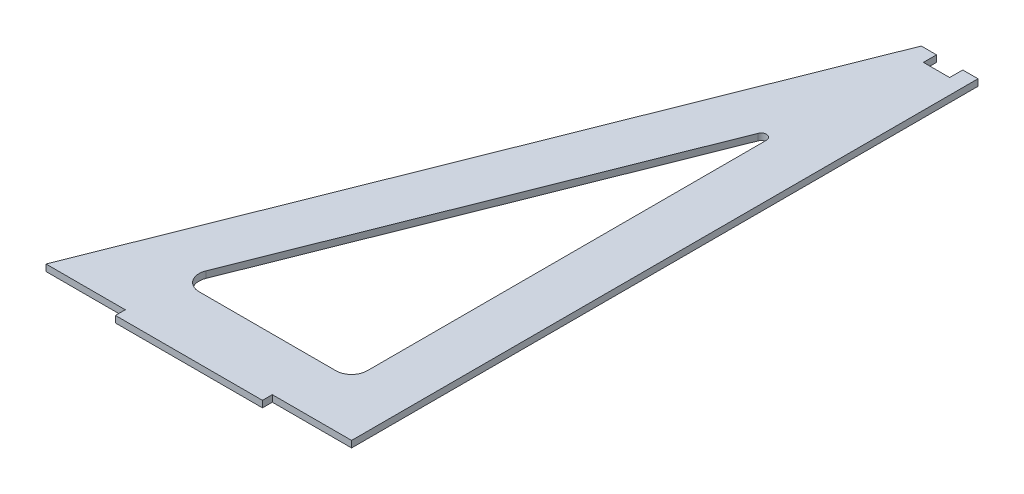
SolidWorks part; units mm, degrees
material "Balsa"
ref_plane "Front Plane" through (0, 0, 0) normal (0, 0, 1) x (1, 0, 0)
ref_plane "Top Plane" through (0, 0, 0) normal (0, 1, 0) x (1, 0, 0)
ref_plane "Right Plane" through (0, 0, 0) normal (1, 0, 0) x (0, 0, -1)
sketch "Sketch1" plane through (0, 0, 0) normal (0, 1, 0) x (1, 0, 0)
  line L0 (0, 0) -> (0, -303.022) construction
  line L1 (0, 0) -> (513.474, 0) construction
  line L2 (0, 0) -> (-147.828, 0)
  line L3 (-147.828, 0) -> (-27.432, 303.022)
  line L4 (-27.432, 303.022) -> (0, 303.022)
  line L5 (0, 303.022) -> (0, 0)
  dimension "D1" = 303.022
  dimension "D2" = 27.432
  dimension "D3" = 147.828
extrude "Boss-Extrude1" add sketch "Sketch1" along normal blind 3.175
sketch "Sketch2" plane through (0, 3.175, 0) normal (0, 1, 0) x (1, 0, 0)
  line L0 (-13.716, 303.022) -> (-13.716, 0) construction
  line L2 (0, 303.022) -> (-27.432, 303.022) construction
  line L3 (-147.828, 0) -> (0, 0) construction
  line L4 (-20.066, 303.022) -> (-20.066, 296.672)
  line L5 (-20.066, 296.672) -> (-7.366, 296.672)
  line L6 (-7.366, 303.022) -> (-20.066, 303.022)
  line L7 (-7.366, 303.022) -> (-7.366, 296.672)
  line L8 (-25.4, 25.4) -> (-25.4, 239.3465)
  line L9 (-25.4, 239.3465) -> (-110.4047, 25.4)
  line L10 (-110.4047, 25.4) -> (-25.4, 25.4)
  line L11 (-25.4, 25.4) -> (-25.4, 239.3465)
  line L12 (-25.4, 239.3465) -> (-110.4047, 25.4)
  line L13 (-110.4047, 25.4) -> (-25.4, 25.4)
  point P13 (-13.716, 296.672)
  dimension "D2" = 6.35
  dimension "D3" = 6.35
  dimension "D1" = 25.4
extrude "Cut-Extrude1" cut sketch "Sketch2" against normal blind 3.175
fillet "Fillet1" radius 7.62 2 edges at (-25.4, 1.5875, -25.4) (-110.4047, 1.5875, -25.4)
fillet "Fillet2" radius 2.54 1 edges at (-25.4, 1.5875, -239.3465)
sketch "Sketch3" plane through (0, 0, 0) normal (0, 0, 1) x (1, 0, 0)
  line L0 (-73.914, 0) -> (-73.914, 3.175) construction
  line L1 (-147.828, 0) -> (0, 0) construction
  line L2 (-147.828, 3.175) -> (0, 3.175) construction
  line L4 (-38.354, 0) -> (-109.474, 0)
  line L5 (-38.354, 0) -> (-38.354, 3.175)
  line L6 (-38.354, 3.175) -> (-109.474, 3.175)
  line L7 (-109.474, 0) -> (-109.474, 3.175)
  line L8 (-38.354, 0) -> (-109.474, 3.175) construction
  line L9 (-38.354, 3.175) -> (-109.474, 0) construction
  point P6 (-73.914, 1.5875)
  dimension "D1" = 71.12
extrude "Boss-Extrude2" add sketch "Sketch3" along normal blind 4.7625
